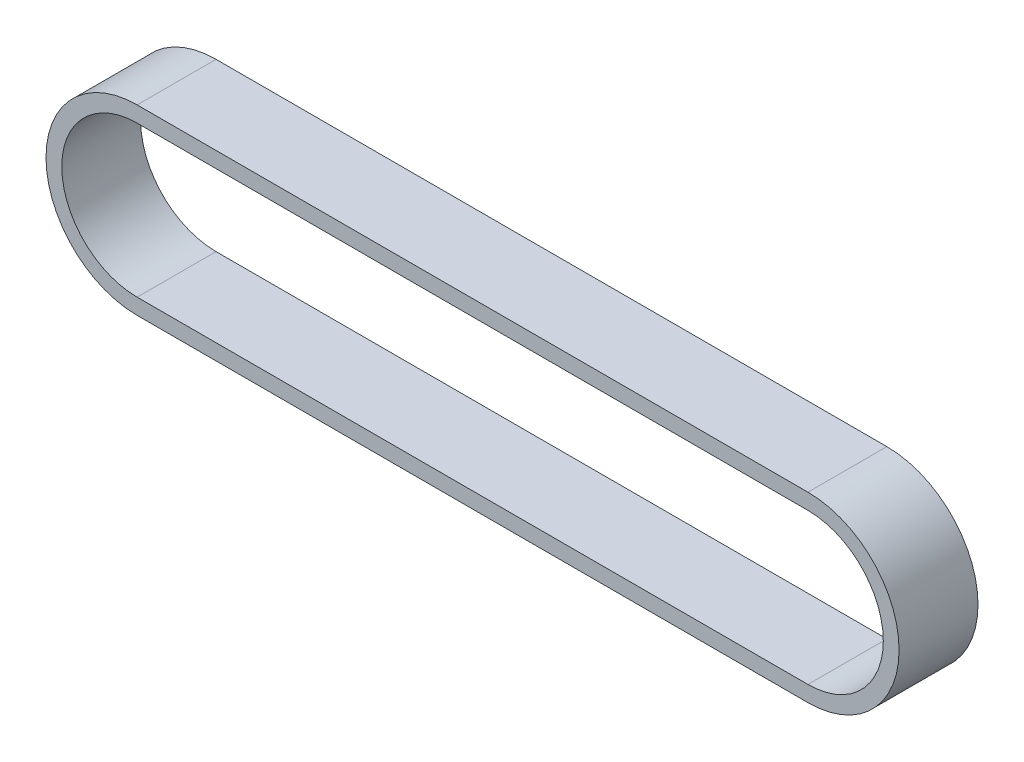
SolidWorks part; units mm, degrees
material "NEOPRENE"
ref_plane "Front" through (0, 0, 0) normal (0, 0, 1) x (1, 0, 0)
ref_plane "Top" through (0, 0, 0) normal (0, 1, 0) x (1, 0, 0)
ref_plane "Right" through (0, 0, 0) normal (1, 0, 0) x (0, 0, -1)
sketch "Sketch2" plane through (0, 0, 0) normal (0, 0, 1) x (1, 0, 0)
  line L0 (0, 0) -> (1, 0) construction
  line L1 (0, 0) -> (0, 1) construction
  line L2 (0, 14.325) -> (127.4967, 14.325)
  line L3 (127.4967, -14.325) -> (0, -14.325)
  arc A0 (0, -14.325) -> (0, 14.325) centre (0, 0) cw
  arc A1 (127.4967, 14.325) -> (127.4967, -14.325) centre (127.4967, 0) cw
extrude "Extrude-Thin1" add sketch "Sketch2" against normal mid plane 15 thin thin type one direction wall 3
